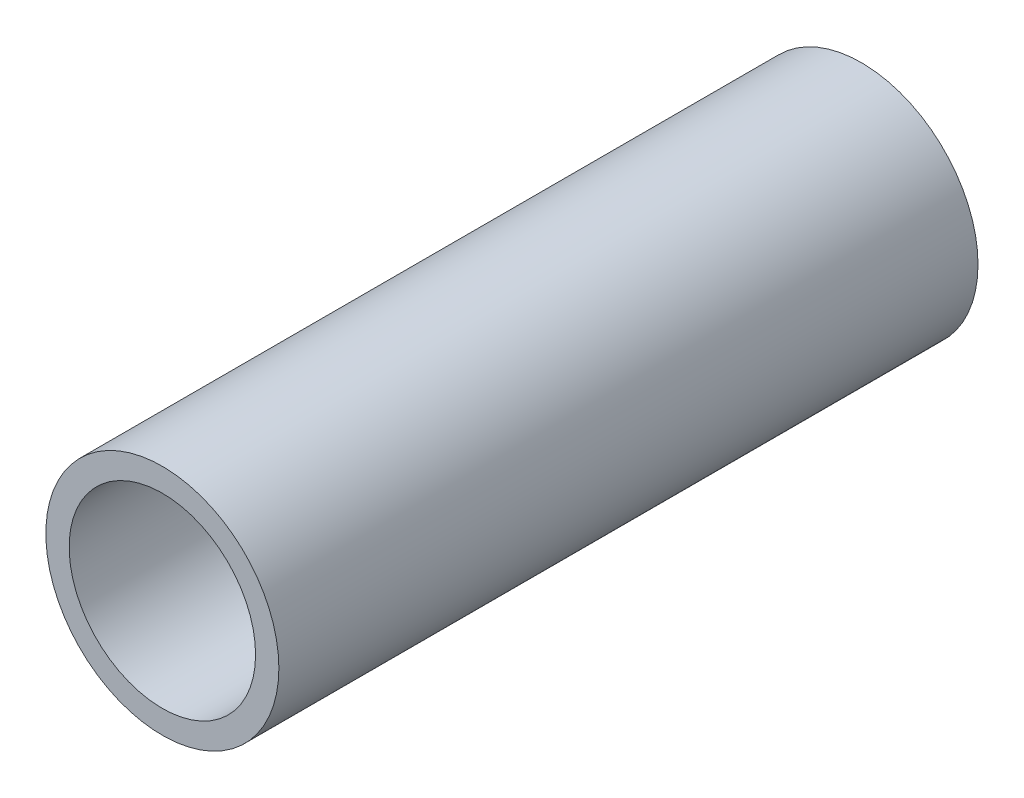
SolidWorks part; units mm, degrees
ref_plane "Front Plane" through (0, 0, 0) normal (0, 0, 1) x (1, 0, 0)
ref_plane "Top Plane" through (0, 0, 0) normal (0, 1, 0) x (1, 0, 0)
ref_plane "Right Plane" through (0, 0, 0) normal (1, 0, 0) x (0, 0, -1)
sketch "Sketch1" plane through (0, 0, 0) normal (0, 0, 1) x (1, 0, 0)
  circle A0 centre (0, 0) radius 25
  circle A1 centre (0, 0) radius 20
  dimension "D1" = 50
  dimension "D2" = 5
extrude "Boss-Extrude1" add sketch "Sketch1" along normal blind 150
ref_plane "Plane1" through (0, -25, 0) normal (0, -1, 0) x (-1, 0, 0)
